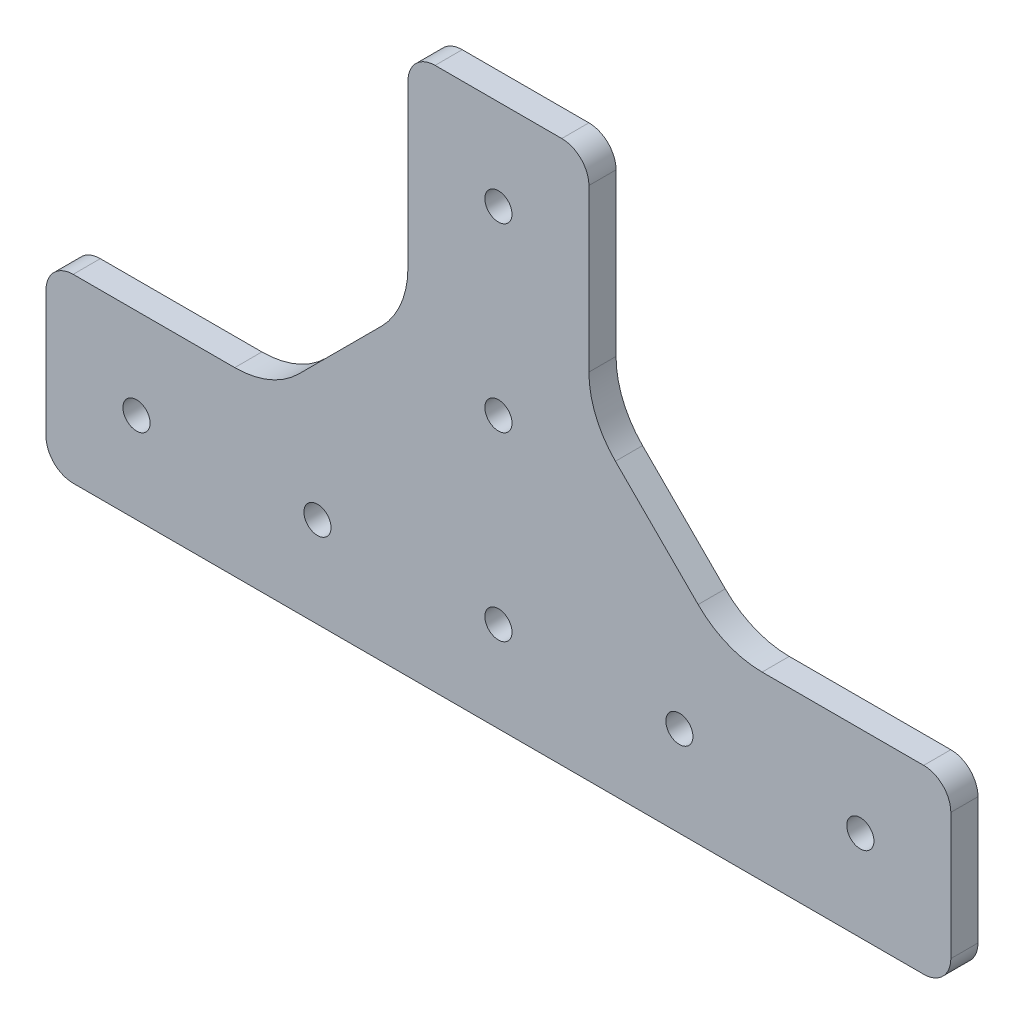
SolidWorks part; units mm, degrees
material "Thornel Mat VMA"
ref_plane "前视基准面" through (0, 0, 0) normal (0, 0, 1) x (1, 0, 0)
ref_plane "上视基准面" through (0, 0, 0) normal (0, 1, 0) x (1, 0, 0)
ref_plane "右视基准面" through (0, 0, 0) normal (1, 0, 0) x (0, 0, -1)
other "Configuration Table"
sketch "草图1" plane through (0, 0, 0) normal (0, 0, 1) x (1, 0, 0)
  line L1 (0, 0) -> (20, 0)
  line L2 (0, 0) -> (0, 60)
  line L3 (0, 60) -> (20, 60)
  line L4 (20, 0) -> (20, 60)
  dimension "D1" = 60
  dimension "D2" = 20
extrude "凸台-拉伸1" add sketch "草图1" along normal blind 3
sketch "草图2" plane through (0, 0, 3) normal (0, 0, 1) x (1, 0, 0)
  line L1 (0, 0) -> (60, 0)
  line L2 (0, 0) -> (0, 20)
  line L3 (0, 20) -> (60, 20)
  line L4 (60, 0) -> (60, 20)
  dimension "D1" = 60
  dimension "D2" = 20
extrude "凸台-拉伸2" add sketch "草图2" against normal blind 3
sketch "草图3" plane through (0, 0, 3) normal (0, 0, 1) x (1, 0, 0)
  line L1 (20, 20) -> (-40, 20)
  line L2 (20, 20) -> (20, 0)
  line L3 (20, 0) -> (-40, 0)
  line L4 (-40, 20) -> (-40, 0)
  dimension "D1" = 20
  dimension "D2" = 60
extrude "凸台-拉伸3" add sketch "草图3" against normal blind 3
sketch "草图4" plane through (0, 0, 3) normal (0, 0, 1) x (1, 0, 0)
  line L0 (10, 60) -> (10, 0) construction
  line L1 (20, 60) -> (0, 60) construction
  line L2 (-40, 0) -> (60, 0) construction
  line L3 (-40, 10) -> (60, 10) construction
  line L4 (-40, 20) -> (-40, 0) construction
  line L5 (60, 0) -> (60, 20) construction
  circle A0 centre (10, 10) radius 1.5
  circle A1 centre (10, 30) radius 1.5
  circle A2 centre (10, 50) radius 1.5
  circle A3 centre (-30, 10) radius 1.5
  circle A4 centre (-10, 10) radius 1.5
  circle A5 centre (30, 10) radius 1.5
  circle A6 centre (50, 10) radius 1.5
  dimension "D1" = 3
  dimension "D2" = 10
  dimension "D3" = 20
  dimension "D4" = 20
  dimension "D5" = 20
  dimension "D6" = 20
  dimension "D7" = 20
  dimension "D8" = 20
extrude "切除-拉伸1" cut sketch "草图4" against normal blind 3
fillet "圆角1" [suppressed] radius 10
fillet "圆角2" radius 3 6 edges at (20, 60, 1.5) (60, 20, 1.5) (60, 0, 1.5) (-40, 0, 1.5) (-40, 20, 1.5) (0, 60, 1.5)
chamfer "倒角1" distance 15 angle 45 2 edges at (20, 20, 1.5) (0, 20, 1.5)
fillet "圆角3" radius 10 4 edges at (35, 20, 1.5) (20, 35, 1.5) (-15, 20, 1.5) (0, 35, 1.5)
